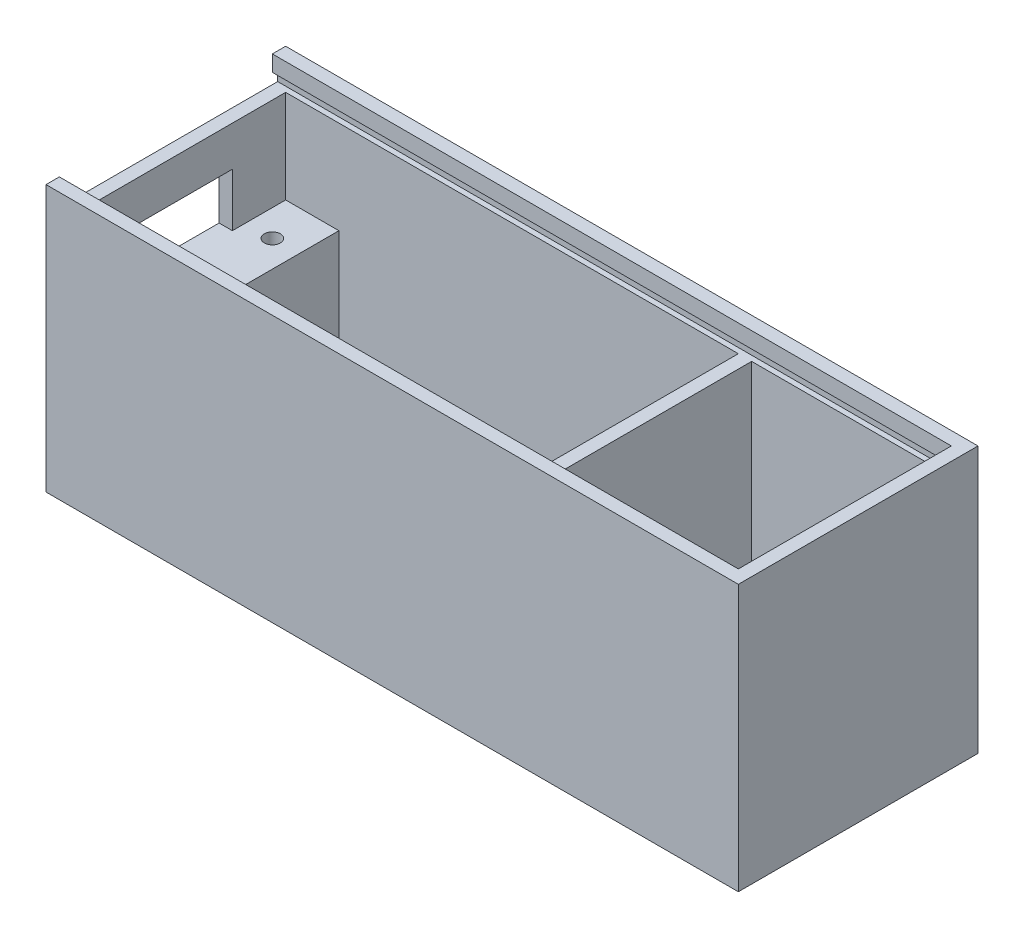
SolidWorks part; units mm, degrees
ref_plane "Front Plane" through (0, 0, 0) normal (0, 0, 1) x (1, 0, 0)
ref_plane "Top Plane" through (0, 0, 0) normal (0, 1, 0) x (1, 0, 0)
ref_plane "Right Plane" through (0, 0, 0) normal (1, 0, 0) x (0, 0, -1)
sketch "Sketch1" plane through (0, 0, 0) normal (0, 1, 0) x (1, 0, 0)
  line L1 (-58.9288, 26.3801) -> (71.0712, 26.3801)
  line L2 (-58.9288, 26.3801) -> (-58.9288, -18.6199)
  line L3 (-58.9288, -18.6199) -> (71.0712, -18.6199)
  line L4 (71.0712, 26.3801) -> (71.0712, -18.6199)
extrude "Boss-Extrude1" add sketch "Sketch1" along normal blind 50
shell "Shell1" thickness 2.5
sketch "Sketch2" plane through (0, 2.5, 0) normal (0, 1, 0) x (1, 0, 0)
  line L0 (-56.4288, -16.1199) -> (68.5712, -16.1199) construction
  line L1 (68.5712, 23.8801) -> (58.5712, 23.8801)
  line L2 (68.5712, 23.8801) -> (68.5712, -16.1199)
  line L3 (68.5712, -16.1199) -> (58.5712, -16.1199)
  line L4 (58.5712, 23.8801) -> (58.5712, -16.1199)
extrude "Boss-Extrude2" add sketch "Sketch2" along normal blind 30
sketch "Sketch4" plane through (0, 2.5, 0) normal (0, 1, 0) x (1, 0, 0)
  line L0 (58.5712, 23.8801) -> (31.0712, 23.8801)
  line L1 (58.5712, 23.8801) -> (-56.4288, 23.8801) construction
sketch "Sketch5" plane through (0, 2.5, 0) normal (0, 1, 0) x (1, 0, 0)
  line L0 (-56.4288, -16.1199) -> (58.5712, -16.1199) construction
  line L1 (31.0712, 23.8801) -> (28.5712, 23.8801)
  line L2 (31.0712, 23.8801) -> (31.0712, -16.1199)
  line L3 (31.0712, -16.1199) -> (28.5712, -16.1199)
  line L4 (28.5712, 23.8801) -> (28.5712, -16.1199)
extrude "Boss-Extrude3" add sketch "Sketch5" along normal blind 47.5
sketch "Sketch6" plane through (0, 2.5, 0) normal (0, 1, 0) x (1, 0, 0)
  line L0 (-56.4288, -16.1199) -> (28.5712, -16.1199) construction
  line L1 (28.5712, 23.8801) -> (18.5712, 23.8801)
  line L2 (28.5712, 23.8801) -> (28.5712, -16.1199)
  line L3 (28.5712, -16.1199) -> (18.5712, -16.1199)
  line L4 (18.5712, 23.8801) -> (18.5712, -16.1199)
extrude "Boss-Extrude4" add sketch "Sketch6" along normal blind 20
sketch "Sketch7" plane through (0, 2.5, 0) normal (0, 1, 0) x (1, 0, 0)
  line L0 (-56.4288, -16.1199) -> (18.5712, -16.1199) construction
  line L1 (-56.4288, 23.8801) -> (-46.4288, 23.8801)
  line L2 (-56.4288, 23.8801) -> (-56.4288, -16.1199)
  line L3 (-56.4288, -16.1199) -> (-46.4288, -16.1199)
  line L4 (-46.4288, 23.8801) -> (-46.4288, -16.1199)
extrude "Boss-Extrude5" add sketch "Sketch7" along normal blind 25
sketch "Sketch8" plane through (-56.4288, 0, 0) normal (1, 0, 0) x (0, 0, -1)
  line L0 (23.8801, 27.5) -> (-16.1199, 50)
  line L1 (23.8801, 50) -> (-16.1199, 27.5)
  line L2 (-16.1199, 50) -> (-16.1199, 27.5) construction
  line L3 (23.8801, 27.5) -> (-16.1199, 27.5) construction
  line L4 (3.8801, 50) -> (3.8801, 27.5)
  line L5 (23.8801, 50) -> (-16.1199, 50) construction
  circle A0 centre (3.8801, 27.5) radius 10
  point P16 (13.8801, 27.5)
  point P17 (-6.1199, 27.5)
  point P19 (0, 0)
sketch "Sketch9" plane through (-56.4288, 0, 0) normal (1, 0, 0) x (0, 0, -1)
  line L1 (13.8801, 27.5) -> (-6.1199, 27.5)
  line L2 (13.8801, 27.5) -> (13.8801, 37.5)
  line L3 (13.8801, 37.5) -> (-6.1199, 37.5)
  line L4 (-6.1199, 27.5) -> (-6.1199, 37.5)
extrude "Cut-Extrude1" cut sketch "Sketch9" against normal blind 2.5
sketch "Sketch10" plane through (18.5712, 0, 0) normal (-1, 0, 0) x (0, 0, 1)
  line L0 (-23.8801, 2.5) -> (16.1199, 22.5)
  line L1 (16.1199, 2.5) -> (-23.8801, 22.5)
  line L2 (-3.8801, 22.5) -> (-3.8801, 2.5)
  line L3 (-23.8801, 22.5) -> (16.1199, 22.5) construction
  line L4 (-23.8801, 2.5) -> (16.1199, 2.5) construction
  circle A0 centre (-3.8801, 2.5) radius 7.5
  point P15 (-11.3801, 2.5)
  point P16 (3.6199, 2.5)
sketch "Sketch11" plane through (18.5712, 0, 0) normal (-1, 0, 0) x (0, 0, 1)
  line L1 (-11.3801, 2.5) -> (3.6199, 2.5)
  line L2 (-11.3801, 2.5) -> (-11.3801, 17.5)
  line L3 (-11.3801, 17.5) -> (3.6199, 17.5)
  line L4 (3.6199, 2.5) -> (3.6199, 17.5)
extrude "Cut-Extrude2" cut sketch "Sketch11" against normal blind 12.5
sketch "Sketch12" plane through (-56.4288, 0, 0) normal (1, 0, 0) x (0, 0, -1)
  line L0 (-16.1199, 50) -> (-16.1199, 27.5) construction
  line L1 (23.8801, 50) -> (-16.1199, 50)
  line L2 (23.8801, 50) -> (23.8801, 45)
  line L3 (23.8801, 45) -> (-16.1199, 45)
  line L4 (-16.1199, 50) -> (-16.1199, 45)
extrude "Cut-Extrude3" cut sketch "Sketch12" against normal blind 2.5
sketch "Sketch15" plane through (0, 27.5, 0) normal (0, 1, 0) x (1, 0, 0)
  line L0 (-46.4288, 23.8801) -> (-56.4288, -16.1199)
  line L1 (-46.4288, -16.1199) -> (-56.4288, 23.8801)
  circle A0 centre (-51.4288, 3.8801) radius 12.5
  point P10 (-51.4288, 16.3801)
  point P11 (-51.4288, -8.6199)
sketch "Sketch17" plane through (0, 22.5, 0) normal (0, 1, 0) x (1, 0, 0)
  line L0 (28.5712, 23.8801) -> (18.5712, -16.1199)
  line L1 (18.5712, 23.8801) -> (28.5712, -16.1199)
  circle A0 centre (23.5712, 3.8801) radius 12.5
  point P10 (23.5712, 16.3801)
  point P11 (23.5712, -8.6199)
sketch "Sketch18" plane through (0, 32.5, 0) normal (0, 1, 0) x (1, 0, 0)
  line L0 (68.5712, 23.8801) -> (58.5712, -16.1199)
  line L1 (58.5712, 23.8801) -> (68.5712, -16.1199)
  circle A0 centre (63.5712, 3.8801) radius 7.5
  point P10 (63.5712, 11.3801)
  point P11 (63.5712, -3.6199)
sketch "Sketch20" plane through (0, 32.5, 0) normal (0, 1, 0) x (1, 0, 0)
  circle A0 centre (63.5712, -3.6199) radius 1.5
  circle A1 centre (63.5712, 11.3801) radius 1.5
extrude "Cut-Extrude5" cut sketch "Sketch20" against normal blind 32.5
sketch "Sketch21" plane through (0, 22.5, 0) normal (0, 1, 0) x (1, 0, 0)
  circle A0 centre (23.5712, -8.6199) radius 1.5
  circle A1 centre (23.5712, 16.3801) radius 1.5
extrude "Cut-Extrude6" cut sketch "Sketch21" against normal blind 22.5
sketch "Sketch22" plane through (0, 27.5, 0) normal (0, 1, 0) x (1, 0, 0)
  circle A0 centre (-51.4288, -8.6199) radius 1.5
  circle A1 centre (-51.4288, 16.3801) radius 1.5
extrude "Cut-Extrude7" cut sketch "Sketch22" against normal blind 27.5
sketch "Sketch24" plane through (0, 0, 0) normal (0, -1, 0) x (1, 0, 0)
  circle A0 centre (-51.4288, 8.6199) radius 3
  circle A1 centre (-51.4288, -16.3801) radius 3
  circle A2 centre (23.5712, 8.6199) radius 3
  circle A3 centre (23.5712, -16.3801) radius 3
  circle A4 centre (63.5712, 3.6199) radius 3
  circle A5 centre (63.5712, -11.3801) radius 3
extrude "Cut-Extrude8" cut sketch "Sketch24" against normal blind 5
sketch "Sketch25" plane through (28.5712, 0, 0) normal (-1, 0, 0) x (0, 0, 1)
  line L0 (-23.8801, 50) -> (-23.8801, 22.5) construction
  line L1 (16.1199, 50) -> (-23.8801, 50)
  line L2 (16.1199, 50) -> (16.1199, 45)
  line L3 (16.1199, 45) -> (-23.8801, 45)
  line L4 (-23.8801, 50) -> (-23.8801, 45)
extrude "Cut-Extrude9" cut sketch "Sketch25" against normal blind 2.5
sketch "Sketch26" plane through (0, 0, 16.1199) normal (0, 0, -1) x (-1, 0, 0)
  line L0 (-68.5712, 50) -> (-68.5712, 32.5) construction
  line L1 (58.9288, 45) -> (-68.5712, 45)
  line L2 (58.9288, 45) -> (58.9288, 47)
  line L3 (58.9288, 47) -> (-68.5712, 47)
  line L4 (-68.5712, 45) -> (-68.5712, 47)
sketch "Sketch27" plane through (0, 0, -23.8801) normal (0, 0, 1) x (1, 0, 0)
  line L0 (68.5712, 50) -> (68.5712, 32.5) construction
  line L1 (-58.9288, 45) -> (68.5712, 45)
  line L2 (-58.9288, 45) -> (-58.9288, 47)
  line L3 (-58.9288, 47) -> (68.5712, 47)
  line L4 (68.5712, 45) -> (68.5712, 47)
extrude "Cut-Extrude10" cut sketch "Sketch26" against normal blind 1
extrude "Cut-Extrude11" cut sketch "Sketch27" against normal blind 1
